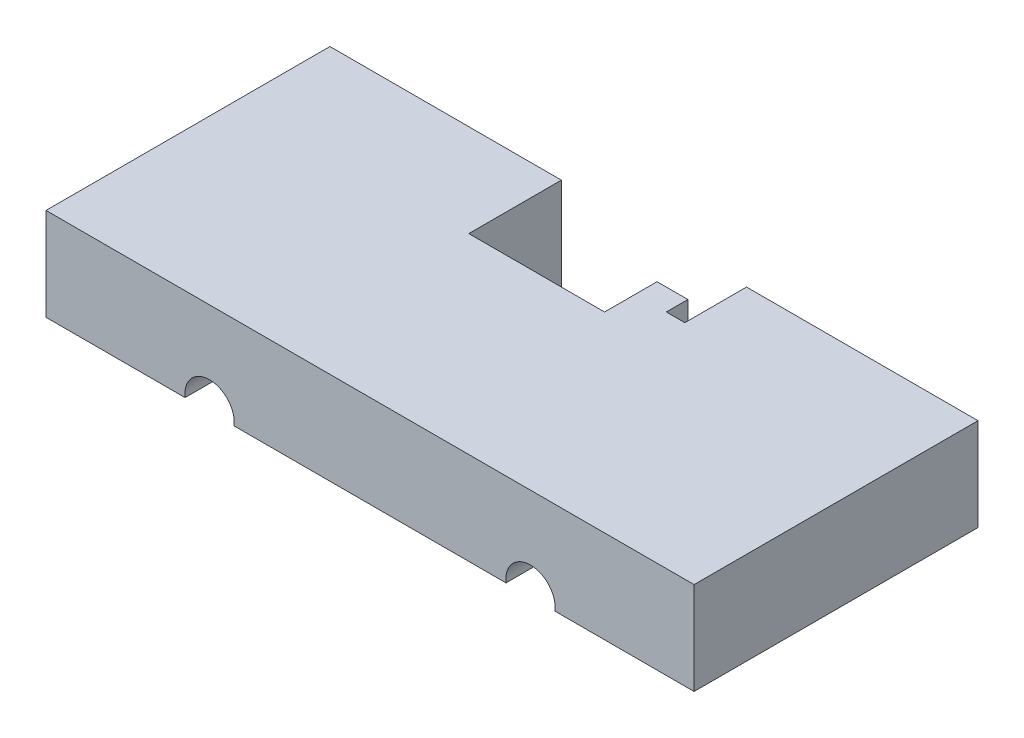
SolidWorks part; units mm, degrees
ref_plane "Front Plane" through (0, 0, 0) normal (0, 0, 1) x (1, 0, 0)
ref_plane "Top Plane" through (0, 0, 0) normal (0, 1, 0) x (1, 0, 0)
ref_plane "Right Plane" through (0, 0, 0) normal (1, 0, 0) x (0, 0, -1)
sketch "Sketch1" plane through (0, 0, 0) normal (0, 1, 0) x (1, 0, 0)
  line L1 (0, 0) -> (105, 0)
  line L2 (0, 0) -> (0, 92)
  line L3 (0, 92) -> (105, 92)
  line L4 (105, 0) -> (105, 92)
  dimension "D1" = 92
  dimension "D2" = 105
extrude "Boss-Extrude1" add sketch "Sketch1" along normal blind 15
sketch "Sketch2" plane through (0, 15, 0) normal (0, 1, 0) x (1, 0, 0)
  line L0 (0, 46) -> (105, 46) construction
  line L1 (0, 92) -> (0, 0) construction
  line L2 (105, 0) -> (105, 92) construction
  line L3 (52.5, 0) -> (52.5, 92) construction
  line L4 (0, 0) -> (105, 0) construction
  line L5 (105, 92) -> (0, 92) construction
  line L7 (67.5, 31) -> (37.5, 31)
  line L8 (67.5, 31) -> (67.5, 61)
  line L9 (67.5, 61) -> (37.5, 61)
  line L10 (37.5, 31) -> (37.5, 61)
  line L11 (67.5, 31) -> (37.5, 61) construction
  line L12 (67.5, 61) -> (37.5, 31) construction
  point P12 (52.5, 46)
  dimension "D1" = 30
  dimension "D2" = 30
extrude "Cut-Extrude1" cut sketch "Sketch2" against normal blind 72
ref_plane "Plane5" through (52.5, 0, 0) normal (-1, 0, 0) x (0, 0, 1)
ref_plane "Plane6" through (26.25, 0, 0) normal (-1, 0, 0) x (0, 0, 1)
ref_plane "Plane7" through (78.75, 0, 0) normal (-1, 0, 0) x (0, 0, 1)
ref_plane "Plane8" through (0, 0, -46) normal (0, 0, 1) x (1, 0, 0)
sketch "Sketch15" plane through (0, 15, 0) normal (0, 1, 0) x (1, 0, 0)
  line L0 (0, 46) -> (105, 46) construction
  line L1 (0, 92) -> (0, 0) construction
  line L2 (105, 0) -> (105, 92) construction
  line L4 (72.5, 67) -> (72.5, 46)
  line L5 (72.5, 46) -> (72.5, 25)
  line L7 (72.5, 67) -> (59.5, 67)
  line L8 (67.5, 61) -> (37.5, 61) construction
  line L9 (59.5, 61) -> (59.5, 52.5)
  line L10 (59.5, 52.5) -> (64.5, 52.5)
  line L11 (64.5, 52.5) -> (64.5, 56)
  line L12 (64.5, 56) -> (67.5, 56)
  line L13 (67.5, 31) -> (67.5, 61) construction
  line L15 (67.5, 36) -> (64.5, 36)
  line L16 (64.5, 36) -> (64.5, 39.5)
  line L17 (64.5, 39.5) -> (59.5, 39.5)
  line L18 (59.5, 39.5) -> (59.5, 31)
  line L19 (37.5, 31) -> (67.5, 31) construction
  line L21 (59.5, 67) -> (59.5, 61)
  line L22 (59.5, 31) -> (59.5, 25)
  line L23 (59.5, 25) -> (72.5, 25)
  line L25 (67.5, 56) -> (67.5, 46)
  line L26 (67.5, 46) -> (67.5, 36)
  dimension "D1" = 21
  dimension "D2" = 21
  dimension "D3" = 3
  dimension "D4" = 3
  dimension "D5" = 13
  dimension "D6" = 13
  dimension "D7" = 10
  dimension "D8" = 10
  dimension "D9" = 5
  dimension "D10" = 6.5
  dimension "D11" = 6.5
extrude "Boss-Extrude4" add sketch "Sketch15" against normal blind 15
sketch "Sketch18" plane through (0, 0, -46) normal (0, 0, 1) x (1, 0, 0)
  line L0 (52.5, 0.5) -> (52.5, 0) construction
  line L2 (37.5, 0) -> (59.5, 0) construction
  line L3 (0, 0.5) -> (74.5, 0.5) construction
  line L4 (52.5, 0) -> (52.5, 15) construction
  line L5 (0, 15) -> (105, 15) construction
  line L6 (105, 0) -> (0, 0) construction
  circle A0 centre (26.5, 0.5) radius 4
  circle A2 centre (78.5, 0.5) radius 4
  dimension "D2" = 8
  dimension "D4" = 8
  dimension "D1" = 0.5
  dimension "D3" = 26
  dimension "D5" = 26
extrude "Cut-Extrude2" cut sketch "Sketch18" against normal blind 64 and the other way blind 84
sketch "Sketch22" plane through (0, 0, -46) normal (0, 0, 1) x (1, 0, 0)
  circle A0 centre (26.5, 0.5) radius 6
  dimension "D1" = 12
extrude "Cut-Extrude3" cut sketch "Sketch22" against normal blind 10 and the other way blind 10
ref_plane "Plane9" through (0, 0, -69) normal (0, 0, -1) x (-1, 0, 0)
sketch "Sketch23" plane through (0, 0, -69) normal (0, 0, -1) x (-1, 0, 0)
  circle A0 centre (-78.5, 0.5) radius 6
  dimension "D1" = 12
extrude "Cut-Extrude4" cut sketch "Sketch23" against normal blind 10 and the other way blind 10
ref_plane "Plane10" through (0, 0, -23) normal (0, 0, 1) x (1, 0, 0)
sketch "Sketch24" plane through (0, 0, -23) normal (0, 0, 1) x (1, 0, 0)
  circle A0 centre (78.5, 0.5) radius 6
  dimension "D1" = 12
extrude "Cut-Extrude5" cut sketch "Sketch24" against normal blind 10 and the other way blind 10
sketch "Sketch27" plane through (0, 0, 0) normal (-1, 0, 0) x (0, 0, 1)
  text T0 "29"
extrude "Cut-Extrude7" cut sketch "Sketch27" against normal blind 2
sketch "Sketch28" plane through (105, 0, 0) normal (1, 0, 0) x (0, 0, -1)
  text T0 "29"
extrude "Cut-Extrude8" cut sketch "Sketch28" against normal blind 2
sketch "Sketch30" plane through (0, 0, 0) normal (0, -1, 0) x (1, 0, 0)
  line L0 (0, -46) -> (105, -46) construction
  line L1 (0, -92) -> (0, 0) construction
  line L2 (105, 0) -> (105, -92) construction
  line L4 (0, -46) -> (105, -46)
  line L5 (0, -46) -> (0, -92)
  line L6 (0, -92) -> (105, -92)
  line L7 (105, -46) -> (105, -92)
extrude "Cut-Extrude11" cut sketch "Sketch30" against normal blind 40
